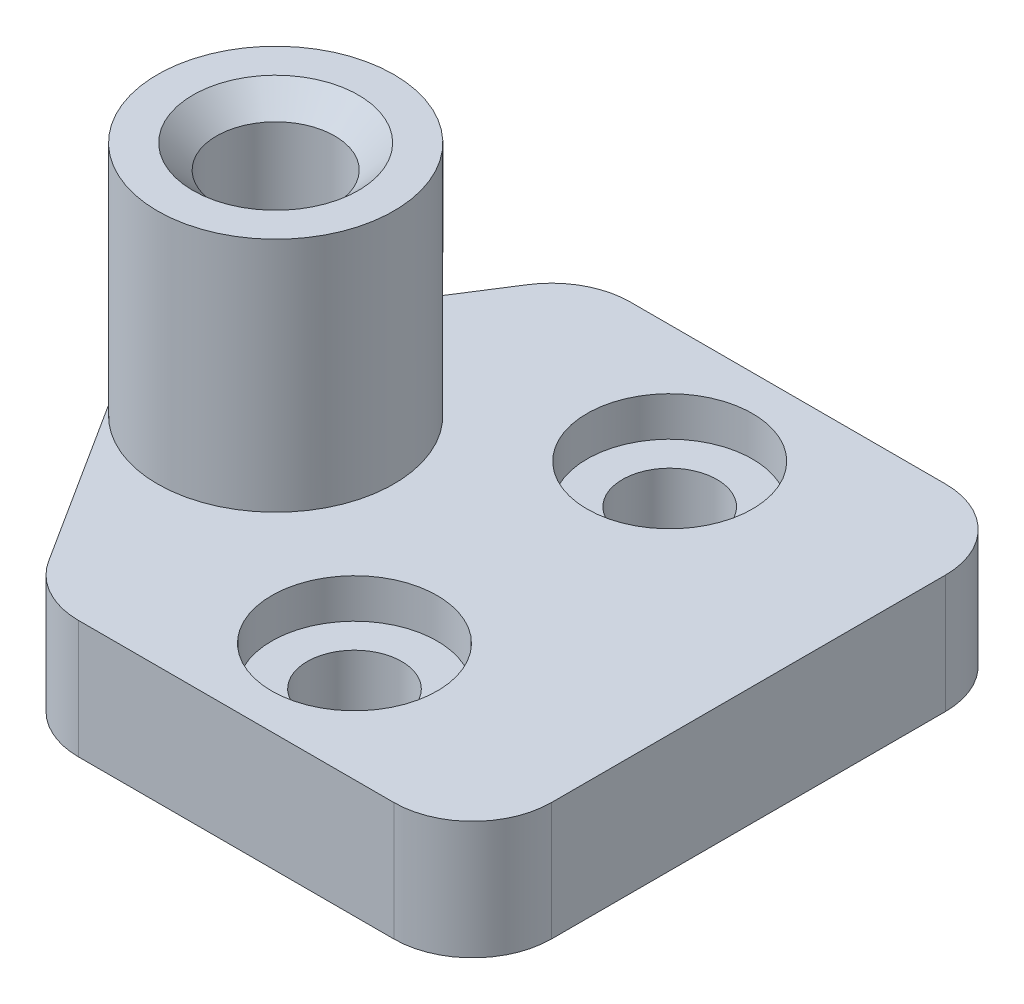
SolidWorks part; units mm, degrees
ref_plane "Front Plane" through (0, 0, 0) normal (0, 0, 1) x (1, 0, 0)
ref_plane "Top Plane" through (0, 0, 0) normal (0, 1, 0) x (1, 0, 0)
ref_plane "Right Plane" through (0, 0, 0) normal (1, 0, 0) x (0, 0, -1)
sketch "Sketch1" plane through (0, 0, 0) normal (0, 1, 0) x (1, 0, 0)
  line L0 (0, 4) -> (-6, 0) construction
  line L1 (-6, 7) -> (6, 7)
  line L2 (-6, 7) -> (-6, -7)
  line L3 (-6, -7) -> (6, -7)
  line L4 (6, 7) -> (6, -7)
  line L5 (0, -7) -> (0, 7) construction
  line L6 (-6, 0) -> (6, 0) construction
  line L7 (-6, 0) -> (0, -4) construction
  circle A0 centre (0, 4) radius 1.2
  circle A1 centre (0, -4) radius 1.2
  point P0 (0, 0)
  dimension "D3" = 2.4
  dimension "D4" = 8
  dimension "D1" = 14
  dimension "D2" = 12
extrude "Boss-Extrude1" add sketch "Sketch1" along normal blind 3
sketch "Sketch3" plane through (0, 3, 0) normal (0, 1, 0) x (1, 0, 0)
  line L0 (-6, 7) -> (-6, -7) construction
  circle A0 centre (-6, 0) radius 3
  dimension "D1" = 6
extrude "Boss-Extrude2" add sketch "Sketch3" along normal blind 6 and the other way up to surface other way up to face at (0, 0, 0)
fillet "Fillet1" radius 2 4 edges at (-6, 1.5, -7) (6, 1.5, -7) (6, 1.5, 7) (-6, 1.5, 7)
sketch "Sketch5" plane through (0, 3, 0) normal (0, 1, 0) x (1, 0, 0)
  line L0 (-8.5301, 1.612) -> (-5.6867, 6.0747)
  line L1 (-8.5301, -1.612) -> (-5.6867, -6.0747)
  line L4 (-6, -5) -> (-6, -3)
  line L5 (-6, 5) -> (-6, 3)
  arc A0 (-6, -5) -> (-4, -7) centre (-4, -5) ccw construction
  arc A1 (-6, 3) -> (-6, -3) centre (-6, 0) ccw construction
  arc A2 (-4, 7) -> (-6, 5) centre (-4, 5) ccw construction
  arc A3 (-8.5301, 1.612) -> (-6, 3) centre (-6, 0) cw
  arc A4 (-8.5301, -1.612) -> (-6, -3) centre (-6, 0) ccw
  arc A5 (-5.6867, -6.0747) -> (-6, -5) centre (-4, -5) cw
  arc A6 (-5.6867, 6.0747) -> (-6, 5) centre (-4, 5) ccw
extrude "Boss-Extrude3" add sketch "Sketch5" against normal up to surface (3 mm away) up to face at (-1.5, 0, 0)
sketch "Sketch6" plane through (0, 3, 0) normal (0, 1, 0) x (1, 0, 0)
  circle A0 centre (0, 4) radius 2.1
  circle A1 centre (0, -4) radius 2.1
  dimension "D1" = 4.2
  dimension "D2" = 4.2
extrude "Cut-Extrude2" cut sketch "Sketch6" against normal blind 1
sketch "Sketch10" plane through (0, 9, 0) normal (0, 1, 0) x (1, 0, 0)
  circle A0 centre (-6, 0) radius 1.5
  dimension "D1" = 3
extrude "Cut-Extrude3" cut sketch "Sketch10" against normal up to surface (6 mm away) up to face at (0, 3, -1.9)
chamfer "Chamfer1" distance 0.6 angle 45 1 edges at (-6, 9, 1.5)
